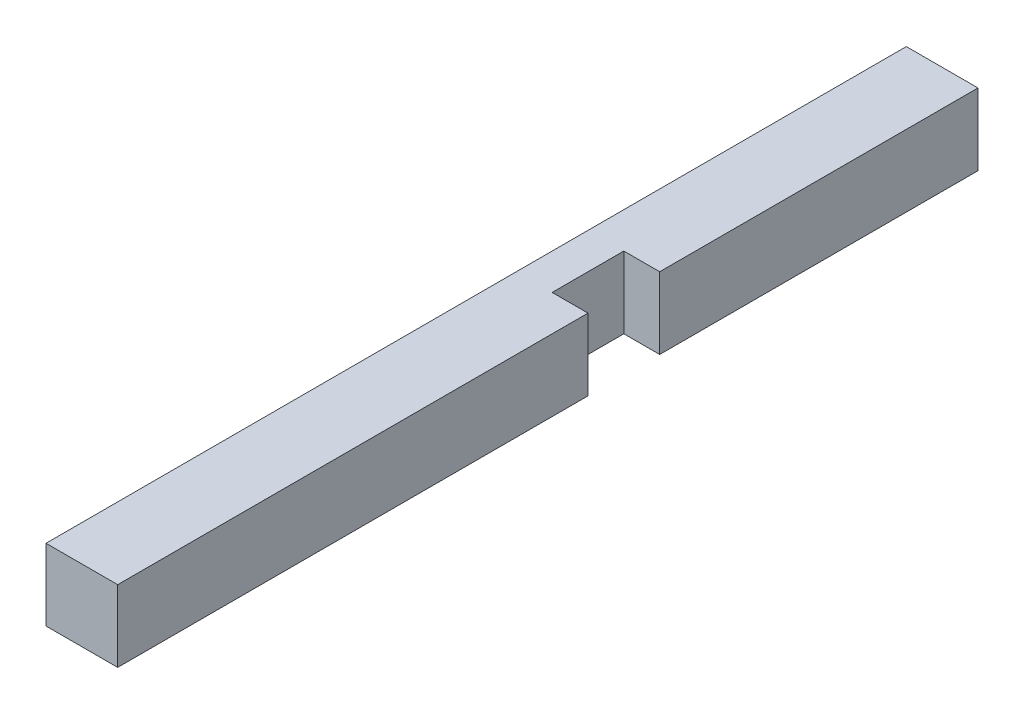
SolidWorks part; units mm, degrees
ref_plane "Plan de face" through (0, 0, 0) normal (0, 0, 1) x (1, 0, 0)
ref_plane "Plan de dessus" through (0, 0, 0) normal (0, 1, 0) x (1, 0, 0)
ref_plane "Plan de droite" through (0, 0, 0) normal (1, 0, 0) x (0, 0, -1)
sketch "Esquisse1" plane through (0, 0, 0) normal (0, 0, 1) x (1, 0, 0)
  line L1 (0, 0) -> (10, 0)
  line L2 (0, 0) -> (0, 10)
  line L3 (0, 10) -> (10, 10)
  line L4 (10, 0) -> (10, 10)
  dimension "D1" = 10
  dimension "D2" = 10
extrude "Boss.-Extru.1" add sketch "Esquisse1" along normal blind 120
sketch "Esquisse2" plane through (0, 10, 0) normal (0, 1, 0) x (1, 0, 0)
  line L0 (10, -120) -> (10, 0) construction
  line L1 (10, -44.4) -> (5, -44.4)
  line L2 (10, -44.4) -> (10, -54.4)
  line L3 (10, -54.4) -> (5, -54.4)
  line L4 (5, -44.4) -> (5, -54.4)
  line L5 (10, 0) -> (0, 0) construction
  point P6 (7.5, -44.4)
  point P9 (5, 0)
  dimension "D1" = 44.4
  dimension "D2" = 10
  dimension "D3" = 5
extrude "Enlèv. mat.-Extru.1" cut sketch "Esquisse2" against normal through all
